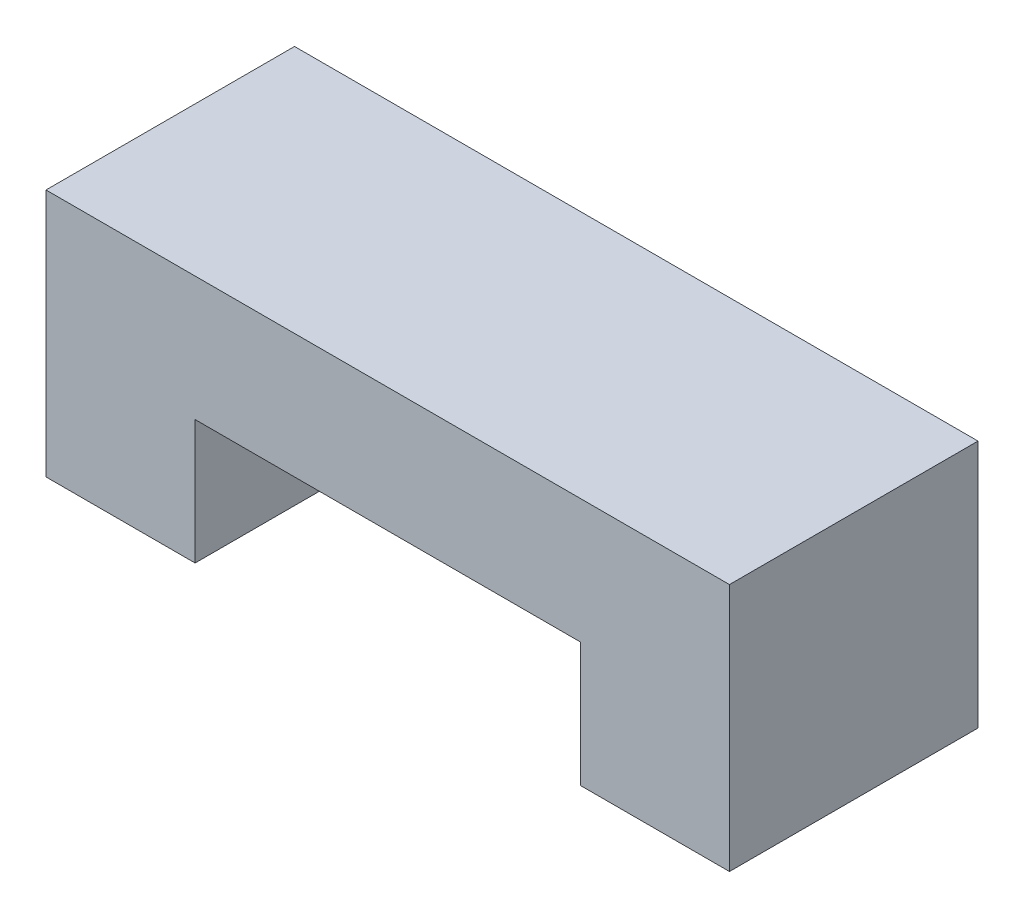
SolidWorks part; units mm, degrees
ref_plane "Front Plane" through (0, 0, 0) normal (0, 0, 1) x (1, 0, 0)
ref_plane "Top Plane" through (0, 0, 0) normal (0, 1, 0) x (1, 0, 0)
ref_plane "Right Plane" through (0, 0, 0) normal (1, 0, 0) x (0, 0, -1)
sketch "Sketch1" plane through (0, 0, 0) normal (0, 0, 1) x (1, 0, 0)
  line L0 (0, 0) -> (12, 0)
  line L1 (12, 0) -> (12, 10)
  line L2 (12, 10) -> (43, 10)
  line L3 (43, 10) -> (43, 0)
  line L4 (43, 0) -> (55, 0)
  line L5 (55, 0) -> (55, 20)
  line L6 (55, 20) -> (0, 20)
  line L7 (0, 20) -> (0, 0)
  dimension "D1" = 12
  dimension "D2" = 55
  dimension "D3" = 20
  dimension "D4" = 10
extrude "Boss-Extrude1" add sketch "Sketch1" along normal blind 20
equation "\"height\"= 20"
equation "\"D3@Sketch1\"=\"height\""
